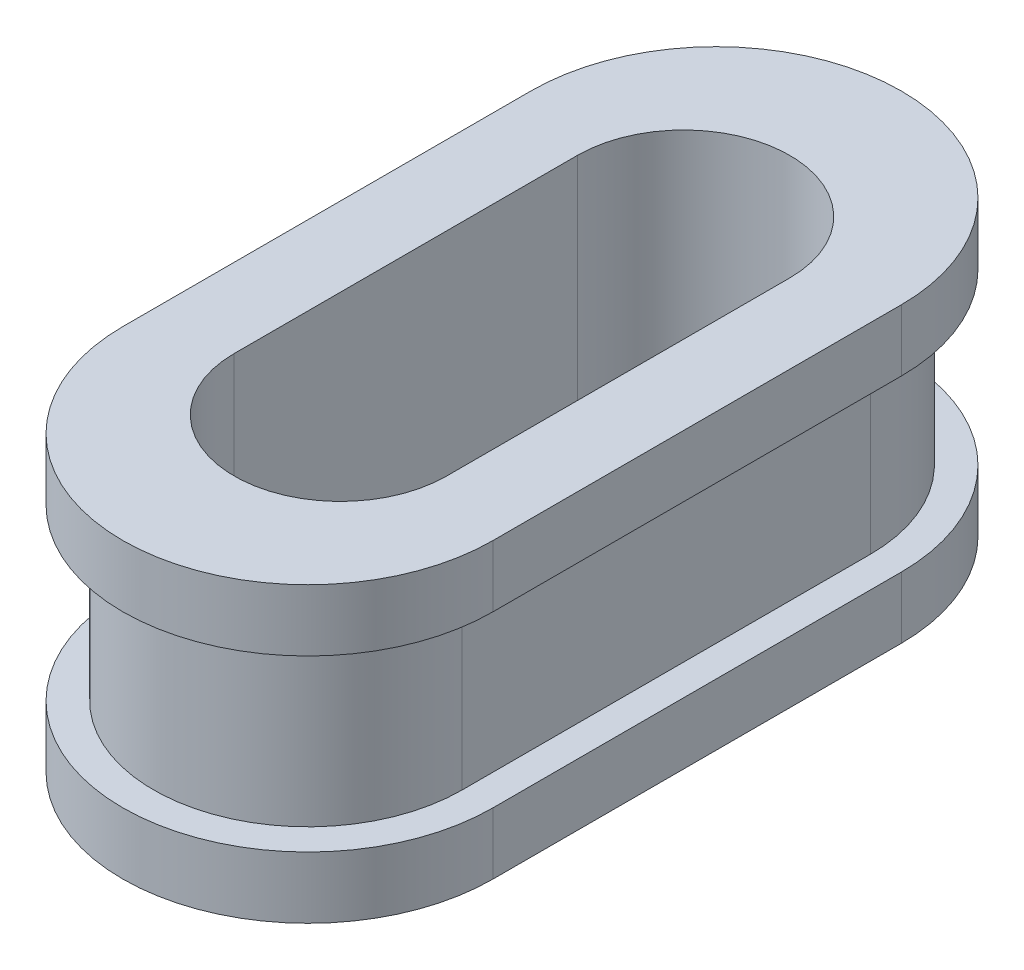
SolidWorks part; units mm, degrees
ref_plane "Front Plane" through (0, 0, 0) normal (0, 0, 1) x (1, 0, 0)
ref_plane "Top Plane" through (0, 0, 0) normal (0, 1, 0) x (1, 0, 0)
ref_plane "Right Plane" through (0, 0, 0) normal (1, 0, 0) x (0, 0, -1)
sketch "Sketch1" plane through (0, 0, 0) normal (0, 1, 0) x (1, 0, 0)
  line L0 (0, 0) -> (0, 104.2857) construction
  line L1 (-30, 104.2857) -> (-30, 38.1557)
  line L2 (30, 104.2857) -> (30, 38.1557)
  arc A0 (30, 104.2857) -> (-30, 104.2857) centre (0, 104.2857) ccw
  arc A1 (-30, 38.1557) -> (30, 38.1557) centre (0, 38.1557) ccw
  dimension "D1" = 60
  dimension "D2" = 66.13
extrude "Boss-Extrude1" add sketch "Sketch1" along normal blind 10
sketch "Sketch2" plane through (0, 10, 0) normal (0, 1, 0) x (1, 0, 0)
  line L0 (0, 0) -> (0, 38.1557) construction
  line L1 (-30, 104.2857) -> (30, 104.2857) construction
  line L2 (-30, 38.1557) -> (30, 38.1557) construction
  line L3 (-25, 104.2857) -> (-25, 38.1557)
  line L4 (25, 104.2857) -> (25, 38.1557)
  line L5 (0, 58.1557) -> (0, 134.2857) construction
  arc A0 (30, 104.2857) -> (-30, 104.2857) centre (0, 104.2857) ccw construction
  arc A1 (25, 104.2857) -> (-25, 104.2857) centre (0, 104.2857) ccw
  arc A2 (-25, 38.1557) -> (25, 38.1557) centre (0, 38.1557) ccw
  dimension "D1" = 50
extrude "Boss-Extrude2" add sketch "Sketch2" along normal blind 27.5
sketch "Sketch3" plane through (0, 37.5, 0) normal (0, 1, 0) x (1, 0, 0)
  line L2 (-30, 104.2857) -> (-30, 38.1557)
  line L3 (30, 38.1557) -> (30, 104.2857)
  line L4 (-30, 104.2857) -> (-30, 38.1557)
  line L5 (30, 38.1557) -> (30, 104.2857)
  arc A2 (30, 104.2857) -> (-30, 104.2857) centre (0, 104.2857) ccw
  arc A3 (-30, 38.1557) -> (30, 38.1557) centre (0, 38.1557) ccw
  arc A4 (30, 104.2857) -> (-30, 104.2857) centre (0, 104.2857) ccw
  arc A5 (-30, 38.1557) -> (30, 38.1557) centre (0, 38.1557) ccw
  dimension "D1" = 0
extrude "Boss-Extrude3" add sketch "Sketch3" along normal blind 10
sketch "Sketch4" plane through (0, 47.5, 0) normal (0, 1, 0) x (1, 0, 0)
  line L0 (0, 0) -> (0, 43.4207) construction
  line L1 (30, 71.2207) -> (-30, 71.2207) construction
  line L2 (30, 38.1557) -> (30, 104.2857) construction
  line L3 (-17.2, 99.0207) -> (-17.2, 43.4207)
  line L4 (17.2, 99.0207) -> (17.2, 43.4207)
  line L5 (0, 99.0207) -> (0, 134.2857) construction
  line L6 (-30, 104.2857) -> (-30, 38.1557) construction
  arc A0 (30, 104.2857) -> (-30, 104.2857) centre (0, 104.2857) ccw construction
  arc A1 (17.2, 99.0207) -> (-17.2, 99.0207) centre (0, 99.0207) ccw
  arc A2 (-17.2, 43.4207) -> (17.2, 43.4207) centre (0, 43.4207) ccw
  dimension "D1" = 17.2
  dimension "D3" = 27.8
  dimension "D2" = 27.8
extrude "Cut-Extrude1" cut sketch "Sketch4" against normal through all both and the other way through all
